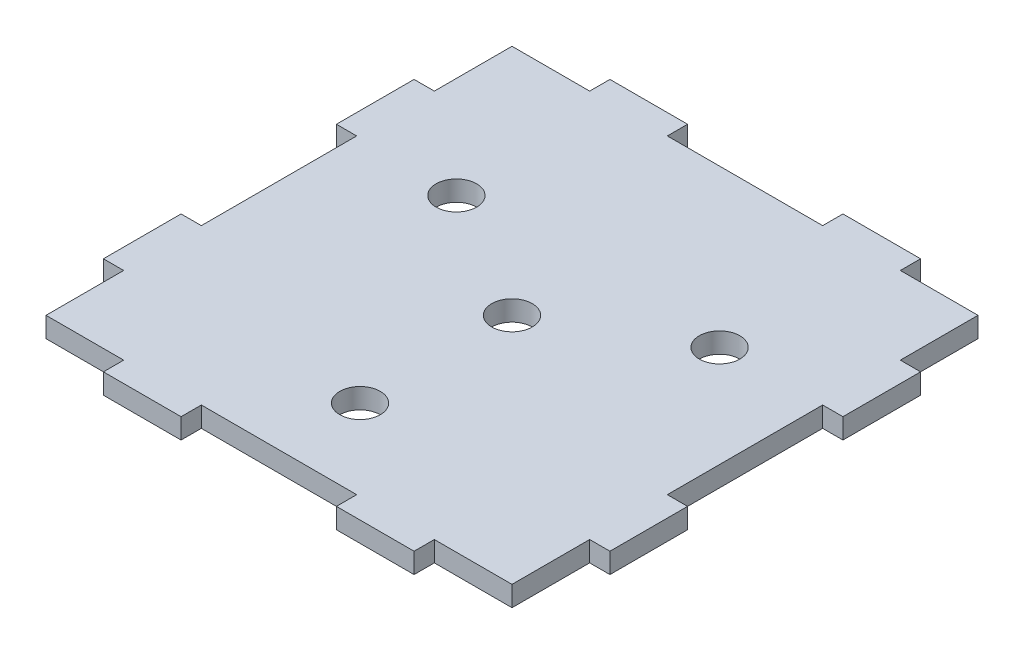
SolidWorks part; units mm, degrees
ref_plane "Front Plane" through (0, 0, 0) normal (0, 0, 1) x (1, 0, 0)
ref_plane "Top Plane" through (0, 0, 0) normal (0, 1, 0) x (1, 0, 0)
ref_plane "Right Plane" through (0, 0, 0) normal (1, 0, 0) x (0, 0, -1)
sketch "Sketch1" plane through (0, 0, 0) normal (0, 1, 0) x (1, 0, 0)
  line L0 (0, 69) -> (-23, 69)
  line L5 (-23, 69) -> (-23, 75)
  line L6 (-23, 75) -> (-46, 75)
  line L7 (-46, 75) -> (-46, 69)
  line L8 (-46, 69) -> (-69, 69)
  line L9 (-69, 69) -> (-69, 46)
  line L10 (-69, 46) -> (-75, 46)
  line L11 (-75, 46) -> (-75, 23)
  line L12 (-75, 23) -> (-69, 23)
  line L13 (-69, 23) -> (-69, 0)
  line L14 (-69, 0) -> (0, 0) construction
  line L15 (0, 69) -> (0, 0) construction
  line L16 (69, 0) -> (69, 23)
  line L17 (69, 23) -> (75, 23)
  line L18 (75, 23) -> (75, 46)
  line L19 (75, 46) -> (69, 46)
  line L20 (69, 46) -> (69, 69)
  line L21 (69, 69) -> (46, 69)
  line L22 (46, 69) -> (46, 75)
  line L23 (46, 75) -> (23, 75)
  line L24 (23, 75) -> (23, 69)
  line L25 (23, 69) -> (0, 69)
  line L26 (0, 69) -> (0, 0) construction
  line L27 (69, 0) -> (0, 0) construction
  line L28 (0, -69) -> (23, -69)
  line L29 (23, -69) -> (23, -75)
  line L30 (23, -75) -> (46, -75)
  line L31 (46, -75) -> (46, -69)
  line L32 (46, -69) -> (69, -69)
  line L33 (69, -69) -> (69, -46)
  line L34 (69, -46) -> (75, -46)
  line L35 (75, -46) -> (75, -23)
  line L36 (75, -23) -> (69, -23)
  line L37 (69, -23) -> (69, 0)
  line L38 (69, 0) -> (0, 0) construction
  line L39 (0, -69) -> (0, 0) construction
  line L40 (-69, 0) -> (-69, -23)
  line L41 (-69, -23) -> (-75, -23)
  line L42 (-75, -23) -> (-75, -46)
  line L43 (-75, -46) -> (-69, -46)
  line L44 (-69, -46) -> (-69, -69)
  line L45 (-69, -69) -> (-46, -69)
  line L46 (-46, -69) -> (-46, -75)
  line L47 (-46, -75) -> (-23, -75)
  line L48 (-23, -75) -> (-23, -69)
  line L49 (-23, -69) -> (0, -69)
  line L50 (0, -69) -> (0, 0) construction
  line L51 (-69, 0) -> (0, 0) construction
  point P5 (-23, 72)
  dimension "D1" = 6
  dimension "D2" = 69
  dimension "D3" = 23
  dimension "D5" = 23
  dimension "D4" = 4
extrude "Boss-Extrude1" add sketch "Sketch1" along normal blind 6
sketch "Sketch2" plane through (0, 6, 0) normal (0, 1, 0) x (1, 0, 0)
  line L0 (0, 69) -> (0, -69) construction
  line L1 (23, 69) -> (-23, 69) construction
  line L2 (-23, -69) -> (23, -69) construction
  circle A0 centre (0, 0) radius 6
  circle A1 centre (0, -45) radius 6
  dimension "D1" = 12
  dimension "D2" = 45
extrude "Cut-Extrude1" cut sketch "Sketch2" against normal through all
pattern_circular "CirPattern1" count 3 over 360 about axis through (0, 0, 0) along (0, 1, 0) of "Cut-Extrude1"
